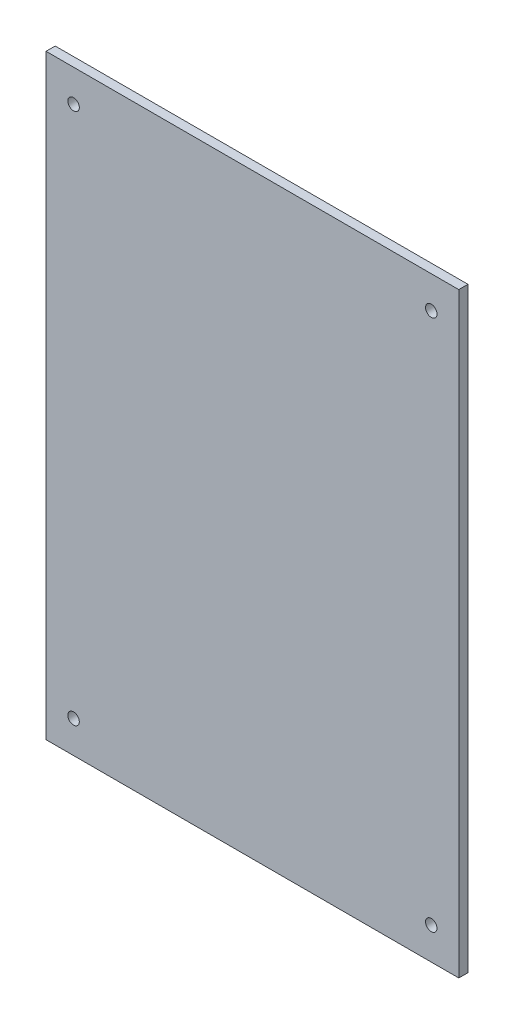
SolidWorks part; units mm, degrees
ref_plane "Front Plane" through (0, 0, 0) normal (0, 0, 1) x (1, 0, 0)
ref_plane "Top Plane" through (0, 0, 0) normal (0, 1, 0) x (1, 0, 0)
ref_plane "Right Plane" through (0, 0, 0) normal (1, 0, 0) x (0, 0, -1)
sketch "Sketch1" plane through (0, 0, 0) normal (0, 0, 1) x (1, 0, 0)
  line L1 (0, 0) -> (180, 0)
  line L2 (0, 0) -> (0, 260)
  line L3 (0, 260) -> (180, 260)
  line L4 (180, 0) -> (180, 260)
  circle A0 centre (12, 14) radius 2.5
  circle A1 centre (12, 246) radius 2.5
  circle A2 centre (168, 14) radius 2.5
  circle A3 centre (168, 246) radius 2.5
  dimension "D1" = 5
  dimension "D2" = 5
  dimension "D3" = 5
  dimension "D4" = 5
  dimension "D5" = 12
  dimension "D6" = 12
  dimension "D7" = 168
  dimension "D8" = 168
  dimension "D9" = 180
  dimension "D10" = 14
  dimension "D11" = 14
  dimension "D12" = 246
  dimension "D13" = 246
  dimension "D14" = 260
extrude "Profile" add sketch "Sketch1" along normal blind 4
equation "\"Profile_Depth\" = 4mm"
equation "\"D1@Profile\" = \"Profile_Depth\""
equation "\"Profile_Sketch_1\" = 5mm"
equation "\"D1@Sketch1\" = \"Profile_Sketch_1\""
equation "\"Profile_Sketch_2\" = 5mm"
equation "\"D2@Sketch1\" = \"Profile_Sketch_2\""
equation "\"Profile_Sketch_3\" = 5mm"
equation "\"D3@Sketch1\" = \"Profile_Sketch_3\""
equation "\"Profile_Sketch_4\" = 5mm"
equation "\"D4@Sketch1\" = \"Profile_Sketch_4\""
equation "\"Profile_Sketch_5\" = 12mm"
equation "\"D5@Sketch1\" = \"Profile_Sketch_5\""
equation "\"Profile_Sketch_6\" = 12mm"
equation "\"D6@Sketch1\" = \"Profile_Sketch_6\""
equation "\"Profile_Sketch_7\" = 168mm"
equation "\"D7@Sketch1\" = \"Profile_Sketch_7\""
equation "\"Profile_Sketch_8\" = 168mm"
equation "\"D8@Sketch1\" = \"Profile_Sketch_8\""
equation "\"Profile_Sketch_9\" = 180mm"
equation "\"D9@Sketch1\" = \"Profile_Sketch_9\""
equation "\"Profile_Sketch_10\" = 14mm"
equation "\"D10@Sketch1\" = \"Profile_Sketch_10\""
equation "\"Profile_Sketch_11\" = 14mm"
equation "\"D11@Sketch1\" = \"Profile_Sketch_11\""
equation "\"Profile_Sketch_12\" = 246mm"
equation "\"D12@Sketch1\" = \"Profile_Sketch_12\""
equation "\"Profile_Sketch_13\" = 246mm"
equation "\"D13@Sketch1\" = \"Profile_Sketch_13\""
equation "\"Profile_Sketch_14\" = 260mm"
equation "\"D14@Sketch1\" = \"Profile_Sketch_14\""
equation "\"EnvelopeWidth\" = 180mm"
equation "\"EnvelopeHeight\" = 260mm"
